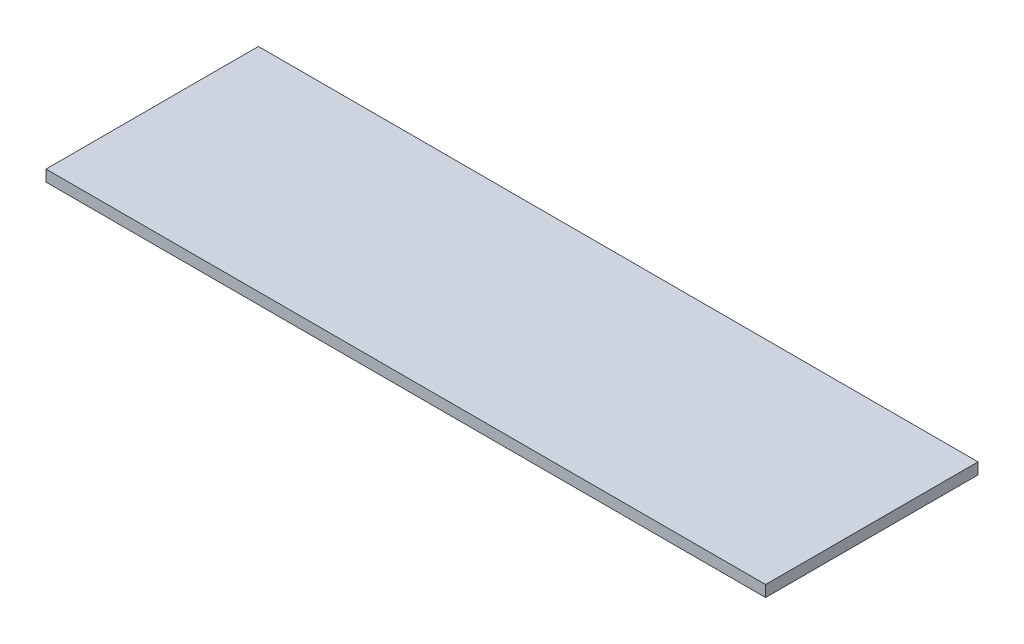
SolidWorks part; units mm, degrees
material "Acrylic (Medium-high impact)"
ref_plane "Front Plane" through (0, 0, 0) normal (0, 0, 1) x (1, 0, 0)
ref_plane "Top Plane" through (0, 0, 0) normal (0, 1, 0) x (1, 0, 0)
ref_plane "Right Plane" through (0, 0, 0) normal (1, 0, 0) x (0, 0, -1)
sketch "Sketch1" plane through (0, 0, 0) normal (0, 1, 0) x (1, 0, 0)
  line L1 (-66.1181, 8.5058) -> (95.5943, 8.5058)
  line L2 (-66.1181, 8.5058) -> (-66.1181, -39.2288)
  line L3 (-66.1181, -39.2288) -> (95.5943, -39.2288)
  line L4 (95.5943, 8.5058) -> (95.5943, -39.2288)
extrude "Extrude1" add sketch "Sketch1" along normal blind 2.54
